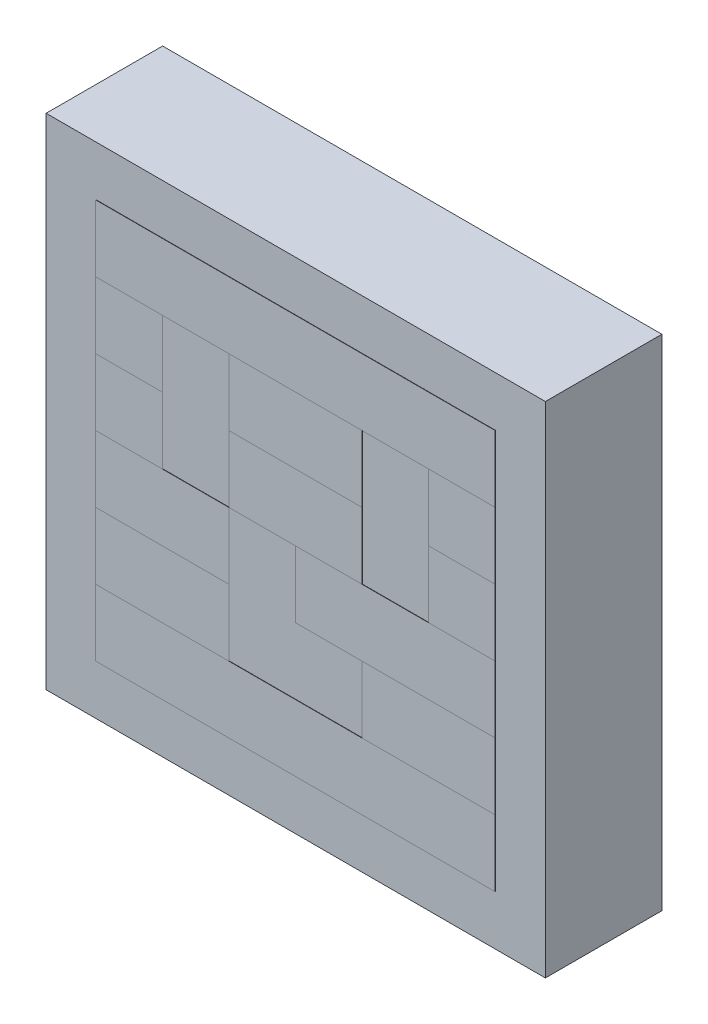
SolidWorks part; units mm, degrees
ref_plane "前视基准面" through (0, 0, 0) normal (0, 0, 1) x (1, 0, 0)
ref_plane "上视基准面" through (0, 0, 0) normal (0, 1, 0) x (1, 0, 0)
ref_plane "右视基准面" through (0, 0, 0) normal (1, 0, 0) x (0, 0, -1)
other "Configuration Table"
sketch "草图1" plane through (0, 0, 0) normal (0, 0, 1) x (1, 0, 0)
  line L1 (-30, -30) -> (30, -30)
  line L2 (-30, -30) -> (-30, 30)
  line L3 (-30, 30) -> (30, 30)
  line L4 (30, -30) -> (30, 30)
  dimension "D1" = 30
  dimension "D2" = 30
  dimension "D3" = 30
extrude "Coplanar_support60x60x14" add sketch "草图1" against normal blind 14
sketch "草图2" plane through (0, 0, 0) normal (0, 0, 1) x (1, 0, 0)
  line L1 (-24, 16) -> (24, 16)
  line L2 (-24, 16) -> (-24, 24)
  line L3 (-24, 24) -> (24, 24)
  line L4 (24, 16) -> (24, 24)
extrude "ID3_row0" add sketch "草图2" along normal blind 0.04 separate body
sketch "草图3" plane through (0, 0, 0) normal (0, 0, 1) x (1, 0, 0)
  line L1 (-24, 8) -> (-16, 8)
  line L2 (-24, 8) -> (-24, 16)
  line L3 (-24, 16) -> (-16, 16)
  line L4 (-16, 8) -> (-16, 16)
  line L6 (-8, 8) -> (8, 8)
  line L7 (-8, 8) -> (-8, 16)
  line L8 (-8, 16) -> (8, 16)
  line L9 (8, 8) -> (8, 16)
  line L11 (16, 8) -> (24, 8)
  line L12 (16, 8) -> (16, 16)
  line L13 (16, 16) -> (24, 16)
  line L14 (24, 8) -> (24, 16)
extrude "ID3_row1" add sketch "草图3" along normal blind 0.04 separate body
sketch "草图4" plane through (0, 0, 0) normal (0, 0, 1) x (1, 0, 0)
  line L1 (-24, 0) -> (-16, 0)
  line L2 (-24, 0) -> (-24, 8)
  line L3 (-24, 8) -> (-16, 8)
  line L4 (-16, 0) -> (-16, 8)
  line L6 (-8, 0) -> (8, 0)
  line L7 (-8, 0) -> (-8, 8)
  line L8 (-8, 8) -> (8, 8)
  line L9 (8, 0) -> (8, 8)
  line L11 (16, 0) -> (24, 0)
  line L12 (16, 0) -> (16, 8)
  line L13 (16, 8) -> (24, 8)
  line L14 (24, 0) -> (24, 8)
extrude "ID3_row2" add sketch "草图4" along normal blind 0.04 separate body
sketch "草图5" plane through (0, 0, 0) normal (0, 0, 1) x (1, 0, 0)
  line L1 (-24, -8) -> (-8, -8)
  line L2 (-24, -8) -> (-24, 0)
  line L3 (-24, 0) -> (-8, 0)
  line L4 (-8, -8) -> (-8, 0)
  line L6 (0, -8) -> (24, -8)
  line L7 (0, -8) -> (0, 0)
  line L8 (0, 0) -> (24, 0)
  line L9 (24, -8) -> (24, 0)
extrude "ID3_row3" add sketch "草图5" along normal blind 0.04 separate body
sketch "草图6" plane through (0, 0, 0) normal (0, 0, 1) x (1, 0, 0)
  line L1 (-24, -16) -> (-8, -16)
  line L2 (-24, -16) -> (-24, -8)
  line L3 (-24, -8) -> (-8, -8)
  line L4 (-8, -16) -> (-8, -8)
  line L6 (8, -16) -> (24, -16)
  line L7 (8, -16) -> (8, -8)
  line L8 (8, -8) -> (24, -8)
  line L9 (24, -16) -> (24, -8)
extrude "ID3_row4" add sketch "草图6" along normal blind 0.04 separate body
sketch "草图7" plane through (0, 0, 0) normal (0, 0, 1) x (1, 0, 0)
  line L1 (-24, -24) -> (24, -24)
  line L2 (-24, -24) -> (-24, -16)
  line L3 (-24, -16) -> (24, -16)
  line L4 (24, -24) -> (24, -16)
extrude "ID3_row5" add sketch "草图7" along normal blind 0.04 separate body
